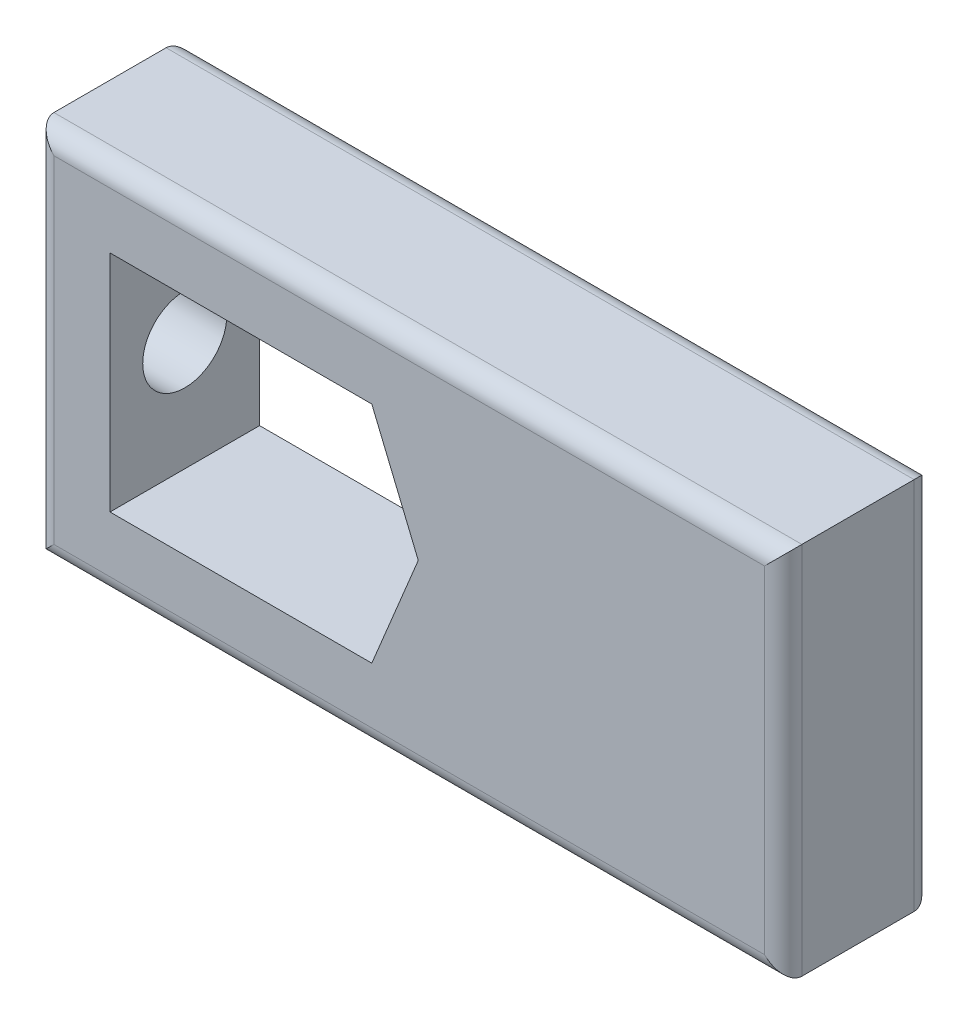
SolidWorks part; units mm, degrees
ref_plane "Přední rovina" through (0, 0, 0) normal (0, 0, 1) x (1, 0, 0)
ref_plane "Horní rovina" through (0, 0, 0) normal (0, 1, 0) x (1, 0, 0)
ref_plane "Pravá rovina" through (0, 0, 0) normal (1, 0, 0) x (0, 0, -1)
sketch "Skica1" plane through (0, 0, 0) normal (0, 0, 1) x (1, 0, 0)
  line L0 (0, 0) -> (0, 20)
  line L1 (0, 20) -> (40, 20)
  line L2 (40, 20) -> (40, 0)
  line L3 (40, 0) -> (0, 0)
  line L4 (4, 16) -> (4, 4)
  line L5 (4, 4) -> (18, 4)
  line L6 (18, 4) -> (20.4853, 10)
  line L7 (20.4853, 10) -> (18, 16)
  line L8 (18, 16) -> (4, 16)
  point P7 (4, 10)
  point P11 (0, 10)
  point P12 (0, 0)
  dimension "D1" = 20
  dimension "D2" = 12
  dimension "D3" = 4
  dimension "D4" = 14
  dimension "D5" = 14
  dimension "D6" = 135
  dimension "D7" = 40
extrude "Přidat vysunutím1" add sketch "Skica1" along normal blind 8
sketch "Skica2" plane through (0, 0, 0) normal (-1, 0, 0) x (0, 0, 1)
  line L0 (8, 20) -> (0, 20) construction
  line L1 (0, 20) -> (0, 0) construction
  circle A0 centre (4, 10) radius 2.25
  point P2 (0, 0)
  point P5 (4, 20)
  point P6 (0, 0)
  point P9 (0, 10)
  dimension "D1" = 4.5
extrude "Odebrat vysunutím1" cut sketch "Skica2" against normal blind 8
fillet "Zaoblit2" radius 1 4 edges at (40, 10, 8) (20, 0, 8) (0, 10, 8) (20, 20, 8)
fillet "Zaoblit3" radius 1 4 edges at (40, 10, 0) (20, 0, 0) (0, 10, 0) (20, 20, 0)
